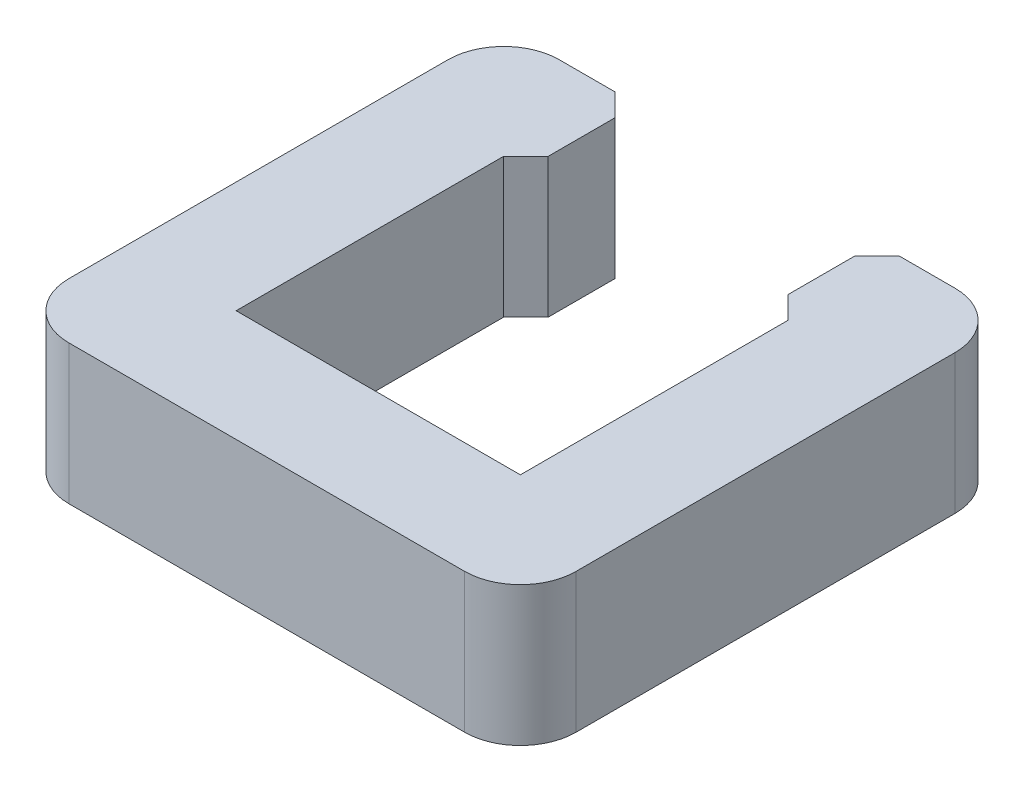
SolidWorks part; units mm, degrees
ref_plane "Front Plane" through (0, 0, 0) normal (0, 0, 1) x (1, 0, 0)
ref_plane "Top Plane" through (0, 0, 0) normal (0, 1, 0) x (1, 0, 0)
ref_plane "Right Plane" through (0, 0, 0) normal (1, 0, 0) x (0, 0, -1)
sketch "Sketch1" plane through (0, 0, 0) normal (0, 1, 0) x (1, 0, 0)
  line L0 (-5.7785, 5.588) -> (-5.7785, -5.588)
  line L1 (-3.2385, 3.048) -> (3.2385, 3.048) construction
  line L2 (-3.2385, 3.048) -> (-3.2385, -3.048)
  line L3 (-3.2385, -3.048) -> (3.2385, -3.048)
  line L4 (3.2385, 3.048) -> (3.2385, -3.048)
  line L5 (-5.7785, -5.588) -> (5.7785, -5.588)
  line L6 (5.7785, 5.588) -> (5.7785, -5.588)
  line L7 (-5.7785, 5.588) -> (-3.2385, 5.588)
  line L8 (-3.2385, 5.588) -> (-3.2385, 3.048) construction
  line L9 (3.2385, 5.588) -> (3.2385, 3.048) construction
  line L10 (3.2385, 5.588) -> (5.7785, 5.588)
  line L11 (-3.2385, 5.588) -> (-2.7305, 5.08)
  line L12 (-5.7785, 5.588) -> (5.7785, 5.588) construction
  line L13 (-2.7305, 5.08) -> (-2.7305, 3.556)
  line L14 (-2.7305, 3.556) -> (-3.2385, 3.048)
  line L15 (0, 3.048) -> (0, 5.54) construction
  line L16 (2.7305, 3.556) -> (3.2385, 3.048)
  line L17 (3.2385, 5.588) -> (2.7305, 5.08)
  line L18 (2.7305, 5.08) -> (2.7305, 3.556)
  point P4 (0, 3.048)
  point P6 (-3.2385, 0)
  dimension "D1" = 6.477
  dimension "D2" = 6.096
  dimension "D4" = 1.524
  dimension "D5" = 0.508
  dimension "D6" = 0.508
  dimension "D3" = 2.54
extrude "Boss-Extrude1" add sketch "Sketch1" along normal blind 3.175
fillet "Fillet1" radius 1.27 4 edges at (-5.7785, 1.5875, -5.588) (5.7785, 1.5875, -5.588) (5.7785, 1.5875, 5.588) (-5.7785, 1.5875, 5.588)
